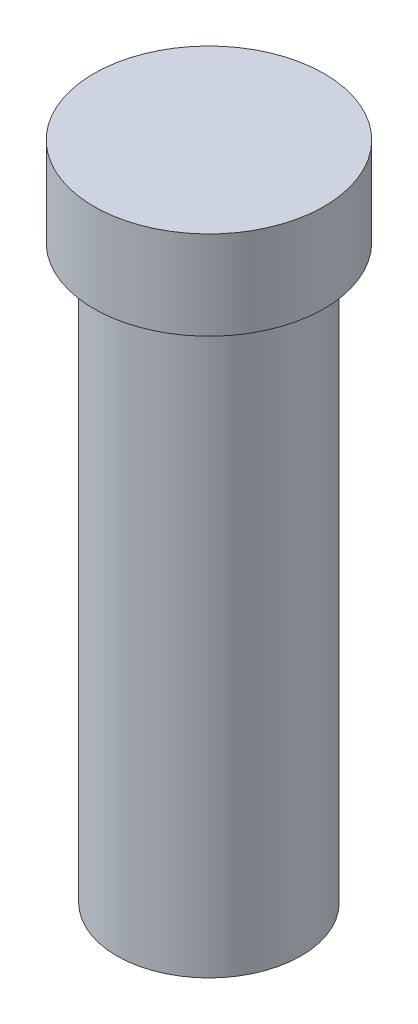
SolidWorks part; units mm, degrees
material "M2 HSS"
ref_plane "Front Plane" through (0, 0, 0) normal (0, 0, 1) x (1, 0, 0)
ref_plane "Top Plane" through (0, 0, 0) normal (0, 1, 0) x (1, 0, 0)
ref_plane "Right Plane" through (0, 0, 0) normal (1, 0, 0) x (0, 0, -1)
sketch "Sketch1" plane through (0, 0, 0) normal (0, 0, 1) x (1, 0, 0)
  line L0 (0, 0) -> (6.5, 0)
  line L1 (6.5, 0) -> (6.5, -5)
  line L2 (6.5, -5) -> (5.2, -5)
  line L3 (5.2, -5) -> (5.2, -37.3)
  line L4 (5.2, -37.3) -> (0, -37.3)
  line L5 (0, -37.3) -> (0, 0)
  line L6 (0, -42.3) -> (0, 5) construction
  dimension "D1" = 5
  dimension "D2" = 5
  dimension "D3" = 10.4
  dimension "D4" = 13
  dimension "D5" = 5
  dimension "D6" = 37.3
revolve "Revolve1" add sketch "Sketch1" angle 360 about L6
